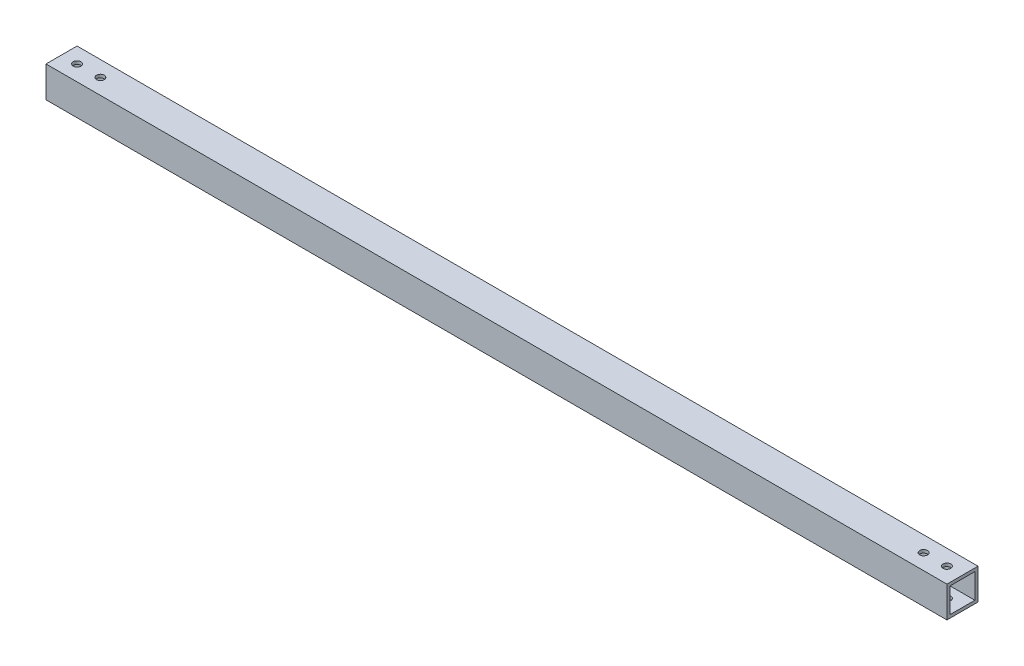
SolidWorks part; units mm, degrees
material "1345 Alloy"
ref_plane "Front Plane" through (0, 0, 0) normal (0, 0, 1) x (1, 0, 0)
ref_plane "Top Plane" through (0, 0, 0) normal (0, 1, 0) x (1, 0, 0)
ref_plane "Right Plane" through (0, 0, 0) normal (1, 0, 0) x (0, 0, -1)
sketch "Sketch1" plane through (0, 0, 0) normal (1, 0, 0) x (0, 0, -1)
  line L1 (-10, 10) -> (10, 10)
  line L2 (-10, 10) -> (-10, -10)
  line L3 (-10, -10) -> (10, -10)
  line L4 (10, 10) -> (10, -10)
  line L5 (-10, 10) -> (10, -10) construction
  line L6 (-10, -10) -> (10, 10) construction
  line L7 (-8, 8) -> (8, 8)
  line L8 (-8, 8) -> (-8, -8)
  line L9 (-8, -8) -> (8, -8)
  line L10 (8, 8) -> (8, -8)
  line L11 (-8, 8) -> (8, -8) construction
  line L12 (-8, -8) -> (8, 8) construction
  point P0 (0, 0)
  point P6 (0, 0)
  dimension "D1" = 20
  dimension "D2" = 20
  dimension "D3" = 16
  dimension "D4" = 16
extrude "Boss-Extrude1" add sketch "Sketch1" along normal blind 580
sketch "Sketch2" plane through (0, 10, 0) normal (0, 1, 0) x (1, 0, 0)
  line L0 (-16.9319, 0) -> (495.2657, 0) construction
  line L1 (580, 10) -> (580, -10) construction
  line L2 (0, 10) -> (0, -10) construction
  line L3 (10, 31.8777) -> (10, -17.8515) construction
  line L4 (570, 25.7534) -> (570, -31.8149) construction
  circle A0 centre (10, 0) radius 2.5
  circle A1 centre (570, 0) radius 2.5
  circle A3 centre (25, 0) radius 2.5
  circle A4 centre (555, 0) radius 2.5
  dimension "D1" = 5
  dimension "D2" = 5
  dimension "D7" = 15
  dimension "D3" = 10
  dimension "D4" = 10
  dimension "D8" = 15
  dimension "D5" = 2
  dimension "D6" = 2
extrude "Cut-Extrude1" cut sketch "Sketch2" against normal through all
